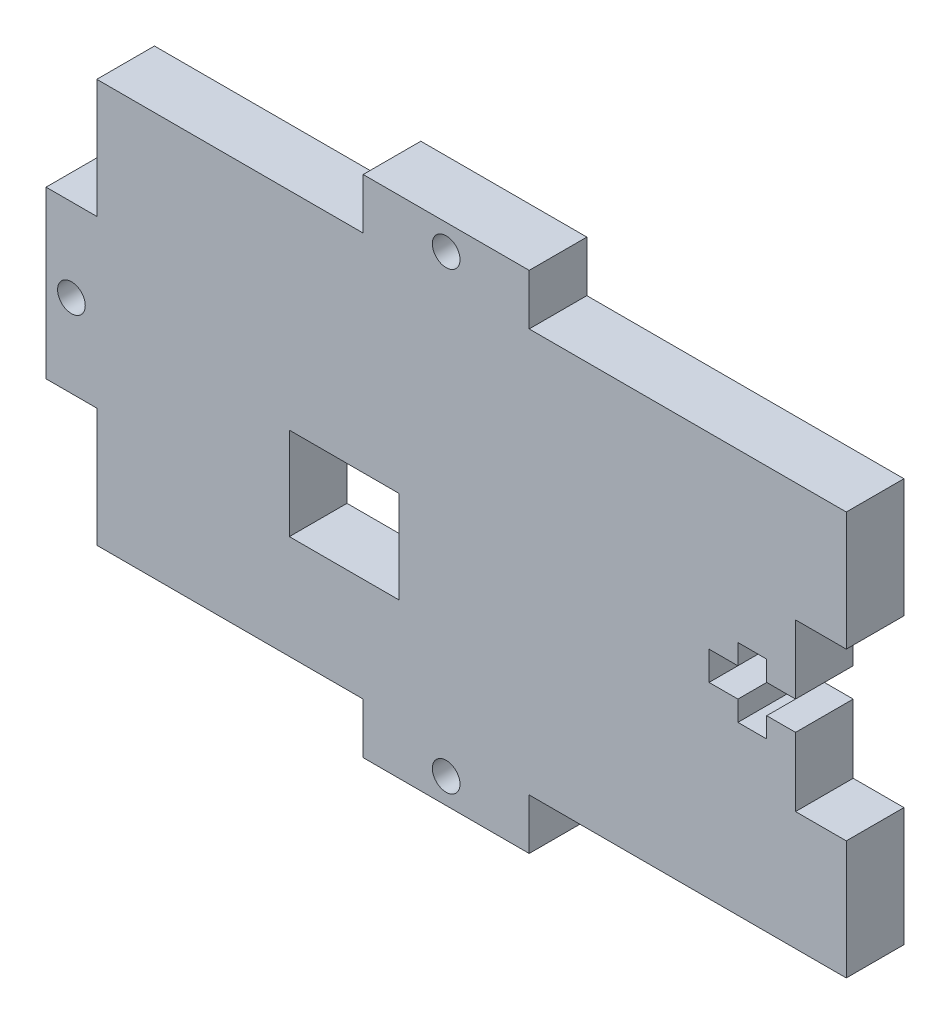
SolidWorks part; units mm, degrees
ref_plane "Front Plane" through (0, 0, 0) normal (0, 0, 1) x (1, 0, 0)
ref_plane "Top Plane" through (0, 0, 0) normal (0, 1, 0) x (1, 0, 0)
ref_plane "Right Plane" through (0, 0, 0) normal (1, 0, 0) x (0, 0, -1)
sketch "Sketch1" plane through (0, 0, 0) normal (0, 0, 1) x (1, 0, 0)
  line L1 (0, 0) -> (82.55, 0)
  line L2 (0, 0) -> (0, 44.45)
  line L3 (0, 44.45) -> (82.55, 44.45)
  line L4 (82.55, 0) -> (82.55, 44.45)
  dimension "D1" = 44.45
  dimension "D2" = 82.55
extrude "Boss-Extrude1" add sketch "Sketch1" along normal blind 6.35
sketch "Sketch2" plane through (0, 0, 6.35) normal (0, 0, 1) x (1, 0, 0)
  line L0 (0, -1.7462) -> (0, 1.7462) construction
  line L1 (0, 31.369) -> (-5.588, 31.369)
  line L2 (0, 31.369) -> (0, 13.081)
  line L3 (0, 13.081) -> (-5.588, 13.081)
  line L4 (-5.588, 31.369) -> (-5.588, 13.081)
  line L6 (0, 44.45) -> (0, 0) construction
  point P6 (-5.588, 22.225)
  point P7 (0, 22.225)
  dimension "D1" = 5.588
  dimension "D2" = 18.288
extrude "Boss-Extrude2" add sketch "Sketch2" against normal blind 6.35
sketch "Sketch5" plane through (0, 0, 6.35) normal (0, 0, 1) x (1, 0, 0)
  line L0 (82.55, 44.45) -> (0, 44.45) construction
  line L1 (29.337, 44.45) -> (47.625, 44.45)
  line L2 (29.337, 44.45) -> (29.337, 50.038)
  line L3 (29.337, 50.038) -> (47.625, 50.038)
  line L4 (47.625, 44.45) -> (47.625, 50.038)
  line L6 (-5.588, 22.225) -> (82.55, 22.225) construction
  line L7 (47.625, 0) -> (47.625, -5.588)
  line L8 (29.337, -5.588) -> (47.625, -5.588)
  line L9 (29.337, 0) -> (29.337, -5.588)
  line L10 (29.337, 0) -> (47.625, 0)
  line L13 (-5.588, 31.369) -> (-5.588, 13.081) construction
  line L14 (82.55, 0) -> (82.55, 44.45) construction
  point P12 (38.481, 0)
  point P18 (38.481, 22.225)
  point P19 (38.481, 44.45)
  dimension "D1" = 18.288
  dimension "D2" = 5.588
extrude "Boss-Extrude3" add sketch "Sketch5" against normal blind 6.35
sketch "Sketch3" plane through (0, 0, 6.35) normal (0, 0, 1) x (1, 0, 0)
  line L0 (82.55, 0) -> (82.55, 44.45) construction
  line L1 (82.55, 13.081) -> (76.962, 13.081)
  line L2 (82.55, 13.081) -> (82.55, 31.369)
  line L3 (82.55, 31.369) -> (76.962, 31.369)
  line L4 (76.962, 13.081) -> (76.962, 31.369)
  line L22 (0, 44.45) -> (0, 31.369)
  line L23 (0, 31.369) -> (-5.588, 31.369)
  line L24 (-5.588, 31.369) -> (-5.588, 13.081)
  line L25 (-5.588, 13.081) -> (0, 13.081)
  line L26 (0, 13.081) -> (0, 0)
  line L27 (0, 0) -> (29.337, 0)
  line L28 (29.337, 0) -> (29.337, -5.588)
  line L29 (29.337, -5.588) -> (47.625, -5.588)
  line L30 (47.625, -5.588) -> (47.625, 0)
  line L31 (47.625, 0) -> (82.55, 0)
  line L32 (82.55, 0) -> (82.55, 44.45)
  line L33 (82.55, 44.45) -> (47.625, 44.45)
  line L34 (47.625, 44.45) -> (47.625, 50.038)
  line L35 (47.625, 50.038) -> (29.337, 50.038)
  line L36 (29.337, 50.038) -> (29.337, 44.45)
  line L37 (29.337, 44.45) -> (0, 44.45)
  line L40 (-5.588, 31.369) -> (-5.588, 13.081) construction
  point P6 (76.962, 22.225)
  point P11 (-5.588, 22.225)
  dimension "D1" = 18.288
  dimension "D2" = 5.588
  dimension "D4" = 0
extrude "Cut-Extrude1" cut sketch "Sketch3" against normal through all
sketch "Sketch6" plane through (0, 0, 6.35) normal (0, 0, 1) x (1, 0, 0)
  line L0 (76.962, 31.369) -> (76.962, 13.081) construction
  line L1 (67.437, 23.8125) -> (70.612, 23.8125)
  line L2 (67.437, 23.8125) -> (67.437, 20.6375)
  line L3 (67.437, 20.6375) -> (70.612, 20.6375)
  line L4 (76.962, 23.8125) -> (76.962, 20.6375)
  line L5 (67.437, 23.8125) -> (76.962, 20.6375) construction
  line L6 (67.437, 20.6375) -> (76.962, 23.8125) construction
  line L7 (70.612, 18.415) -> (73.787, 18.415)
  line L8 (70.612, 18.415) -> (70.612, 20.6375)
  line L9 (70.612, 26.035) -> (73.787, 26.035)
  line L10 (73.787, 18.415) -> (73.787, 20.6375)
  line L11 (70.612, 18.415) -> (73.787, 26.035) construction
  line L12 (70.612, 26.035) -> (73.787, 18.415) construction
  line L13 (70.612, 23.8125) -> (70.612, 26.035)
  line L14 (73.787, 23.8125) -> (76.962, 23.8125)
  line L15 (73.787, 23.8125) -> (73.787, 26.035)
  line L16 (73.787, 20.6375) -> (76.962, 20.6375)
  line L17 (-2.794, 31.369) -> (-2.794, 13.081) construction
  line L18 (0, 31.369) -> (-5.588, 31.369) construction
  line L19 (-5.588, 13.081) -> (0, 13.081) construction
  line L20 (29.337, 50.038) -> (29.337, 44.45) construction
  line L21 (47.625, 44.45) -> (47.625, 50.038) construction
  line L22 (47.625, -5.588) -> (47.625, 0) construction
  line L23 (29.337, 0) -> (29.337, -5.588) construction
  line L24 (29.337, 50.038) -> (29.337, 44.45) construction
  line L25 (47.625, 44.45) -> (47.625, 50.038) construction
  line L26 (47.625, -5.588) -> (47.625, 0) construction
  line L27 (29.337, 0) -> (29.337, -5.588) construction
  line L28 (29.337, 47.244) -> (47.625, 47.244) construction
  line L29 (29.337, -2.794) -> (47.625, -2.794) construction
  circle A0 centre (-2.794, 22.225) radius 1.524
  circle A1 centre (38.481, -2.794) radius 1.524
  circle A2 centre (38.481, 47.244) radius 1.524
  point P0 (72.1995, 22.225)
  point P5 (72.1995, 22.225)
  point P12 (76.962, 22.225)
  dimension "D4" = 3.048
  dimension "D5" = 3.048
  dimension "D6" = 3.048
  dimension "D1" = 3.175
  dimension "D2" = 7.62
  dimension "1/8" = 3.175
  dimension "D3" = 9.525
extrude "Cut-Extrude2" cut sketch "Sketch6" against normal through all
sketch "Sketch7" plane through (0, 0, 0) normal (0, 0, 1) x (1, 0, 0)
  line L0 (11.811, 16.51) -> (65.151, 16.51) construction
  line L2 (3.4926, 0) -> (-3.4926, 0) construction
  line L3 (21.209, 11.43) -> (33.274, 11.43)
  line L4 (21.209, 11.43) -> (21.209, 21.59)
  line L5 (21.209, 21.59) -> (33.274, 21.59)
  line L6 (33.274, 11.43) -> (33.274, 21.59)
  line L7 (21.209, 11.43) -> (33.274, 21.59) construction
  line L8 (21.209, 21.59) -> (33.274, 11.43) construction
  line L11 (0, -1.7462) -> (0, 1.7462) construction
  point P2 (27.2415, 16.51)
  point P3 (38.481, 16.51)
  point P4 (38.481, 50.038)
  point P5 (27.2415, 16.51)
  dimension "D1" = 53.34
  dimension "D2" = 15.4305
  dimension "D3" = 12.065
  dimension "D4" = 10.16
  dimension "D5" = 11.43
  dimension "D6" = 21.209
extrude "Cut-Extrude4" cut sketch "Sketch7" along normal through all
